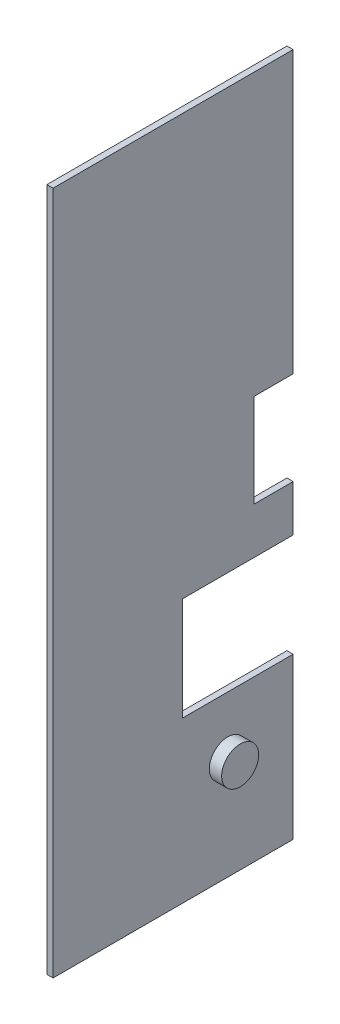
SolidWorks part; units mm, degrees
ref_plane "Спереди" through (0, 0, 0) normal (0, 0, 1) x (1, 0, 0)
ref_plane "Сверху" through (0, 0, 0) normal (0, 1, 0) x (1, 0, 0)
ref_plane "Справа" through (0, 0, 0) normal (1, 0, 0) x (0, 0, -1)
ref_plane "Плоскость4" through (0.5, 0, 0) normal (-1, 0, 0) x (0, -1, 0)
sketch "Эскиз1" plane through (0.5, 0, 0) normal (-1, 0, 0) x (0, -1, 0)
  line L0 (9.85, 42.25) -> (-100.85, 42.25)
  line L1 (-100.85, 42.25) -> (-100.85, 3.4)
  line L2 (-100.85, 3.4) -> (9.85, 3.4)
  line L3 (9.85, 3.4) -> (9.85, 42.25)
extrude "Бобышка-Вытянуть1" add sketch "Эскиз1" against normal blind 0.5
sketch "Эскиз2" plane through (0.5, 0, 0) normal (-1, 0, 0) x (0, 0, 1)
  line L0 (42.25, -9.85) -> (3.4, -9.85)
  line L1 (3.4, -9.85) -> (3.4, 100.85)
  line L2 (3.4, 100.85) -> (42.25, 100.85)
  line L3 (42.25, 100.85) -> (42.25, -9.85)
extrude "Бобышка-Вытянуть2" add sketch "Эскиз2" along normal blind 0.5
sketch "Эскиз3" plane through (0, 0, 0) normal (-1, 0, 0) x (0, 0, 1)
  line L0 (3.4, 100.85) -> (3.4, -9.85) construction
  line L1 (3.4, 32.8159) -> (21.3328, 32.8159)
  line L2 (3.4, 32.8159) -> (3.4, 16.1071)
  line L3 (3.4, 16.1071) -> (21.3328, 16.1071)
  line L4 (21.3328, 32.8159) -> (21.3328, 16.1071)
extrude "Вырез-Вытянуть1" cut sketch "Эскиз3" against normal blind 10
sketch "Эскиз4" plane through (0, 0, 0) normal (-1, 0, 0) x (0, 0, 1)
  line L0 (3.4, 100.85) -> (3.4, 32.8159) construction
  line L1 (3.4, 55.4013) -> (9.7385, 55.4013)
  line L2 (3.4, 55.4013) -> (3.4, 40.3057)
  line L3 (3.4, 40.3057) -> (9.7385, 40.3057)
  line L4 (9.7385, 55.4013) -> (9.7385, 40.3057)
extrude "Вырез-Вытянуть2" cut sketch "Эскиз4" against normal blind 3
sketch "Эскиз5" plane through (0, 0, 0) normal (-1, 0, 0) x (0, 0, 1)
  circle A0 centre (13.9679, 6.8056) radius 1.3797
extrude "Вырез-Вытянуть3" cut sketch "Эскиз5" against normal blind 3
sketch "Эскиз6" plane through (1, 0, 0) normal (1, 0, 0) x (0, 0, -1)
  circle A0 centre (-13.9679, 6.8056) radius 2.2735
  circle A1 centre (-13.9679, 6.8056) radius 3
extrude "Бобышка-Вытянуть3" add sketch "Эскиз6" along normal blind 1
sketch "Эскиз7" plane through (2, 0, 0) normal (1, 0, 0) x (0, 0, -1)
  circle A0 centre (-13.9679, 6.8056) radius 3
extrude "Бобышка-Вытянуть4" add sketch "Эскиз7" along normal blind 1
